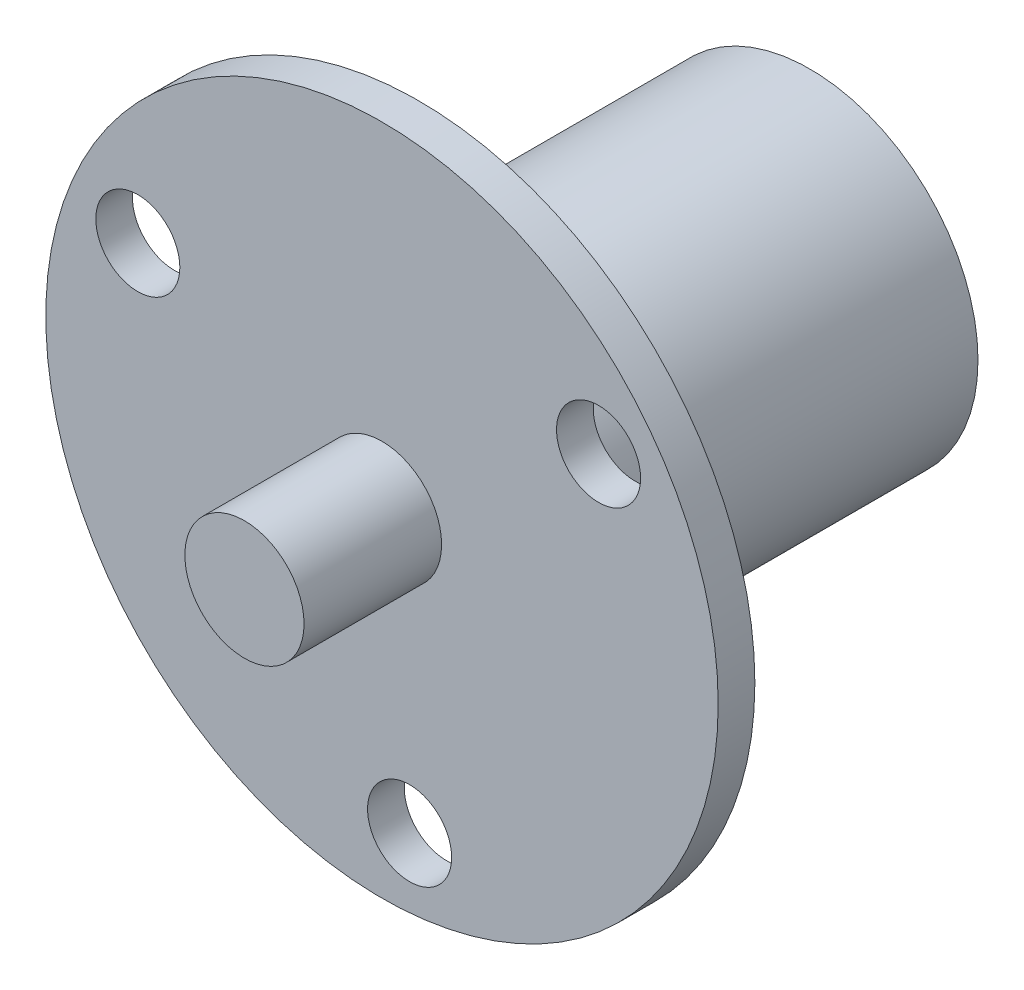
SolidWorks part; units mm, degrees
ref_plane "Front Plane" through (0, 0, 0) normal (0, 0, 1) x (1, 0, 0)
ref_plane "Top Plane" through (0, 0, 0) normal (0, 1, 0) x (1, 0, 0)
ref_plane "Right Plane" through (0, 0, 0) normal (1, 0, 0) x (0, 0, -1)
sketch "Sketch1" plane through (0, 0, 0) normal (0, 0, 1) x (1, 0, 0)
  circle A0 centre (0, 0) radius 11
  dimension "D1" = 22
extrude "Boss-Extrude1" add sketch "Sketch1" along normal blind 25.6
sketch "Sketch2" plane through (0, 0, 25.6) normal (0, 0, 1) x (1, 0, 0)
  circle A0 centre (0, 0) radius 22
  dimension "D1" = 44
extrude "Boss-Extrude2" add sketch "Sketch2" along normal blind 2.4
sketch "Sketch3" plane through (0, 0, 28) normal (0, 0, 1) x (1, 0, 0)
  circle A0 centre (0, 0) radius 3.9
  dimension "D1" = 7.8
extrude "Boss-Extrude3" add sketch "Sketch3" along normal blind 9
sketch "Sketch4" plane through (0, 0, 28) normal (0, 0, 1) x (1, 0, 0)
  circle A0 centre (0, 0) radius 17.5
  circle A1 centre (-15.9779, 7.1384) radius 2.75
  circle A2 centre (14.171, 10.2681) radius 2.75
  circle A3 centre (1.8069, -17.4065) radius 2.75
  point P12 (0, 0)
  dimension "D1" = 35
  dimension "D2" = 5.5
  dimension "D3" = 3
extrude "Cut-Extrude1" cut sketch "Sketch4" against normal blind 9 contours A0 A1 | A0 A1 | A0 A2 | A0 A2 | A0 A3 | A0 A3
